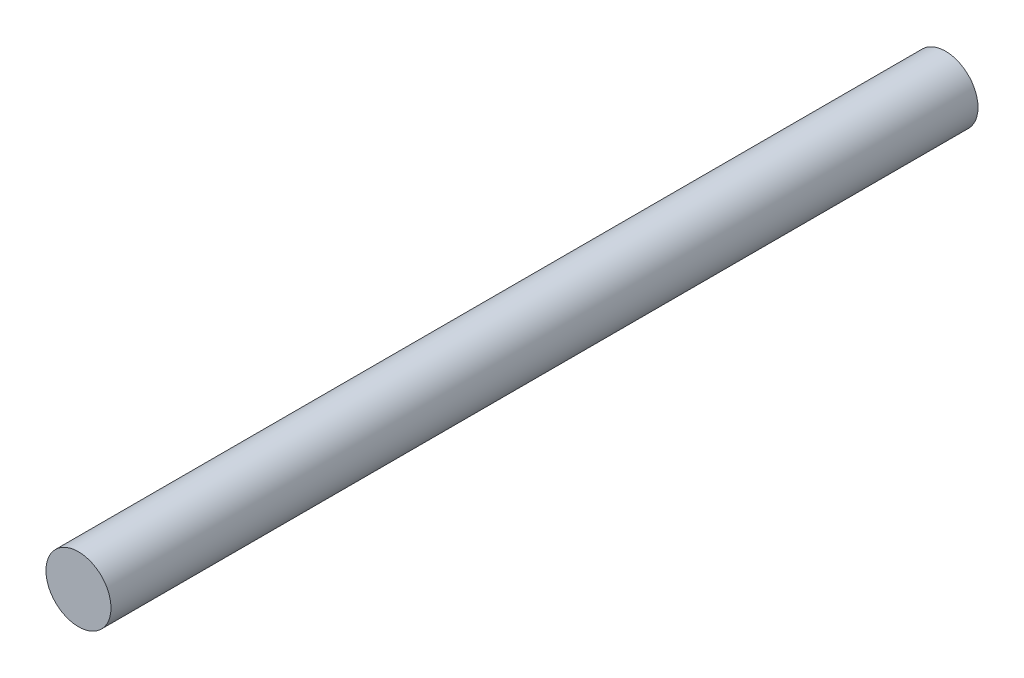
SolidWorks part; units mm, degrees
ref_plane "Front" through (0, 0, 0) normal (0, 0, 1) x (1, 0, 0)
ref_plane "Top" through (0, 0, 0) normal (0, 1, 0) x (1, 0, 0)
ref_plane "Right" through (0, 0, 0) normal (1, 0, 0) x (0, 0, -1)
sketch "Эскиз1" plane through (0, 0, 0) normal (0, 0, 1) x (1, 0, 0)
  circle A0 centre (0, 0) radius 1.5
  dimension "D1" = 3
extrude "Бобышка-Вытянуть1" add sketch "Эскиз1" along normal blind 40
